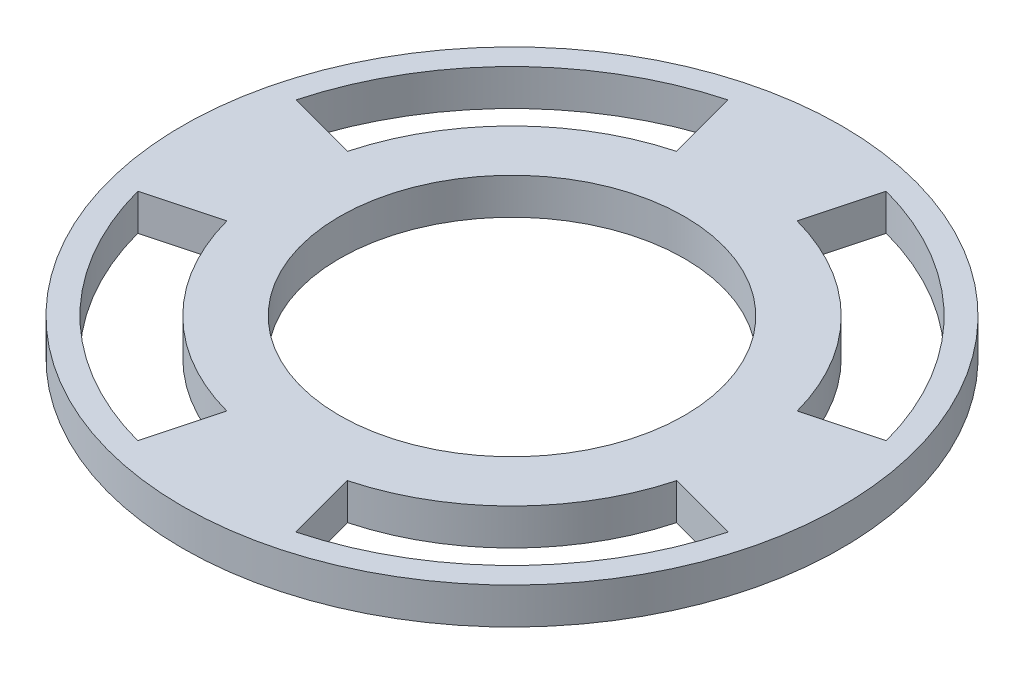
SolidWorks part; units mm, degrees
ref_plane "Front Plane" through (0, 0, 0) normal (0, 0, 1) x (1, 0, 0)
ref_plane "Top Plane" through (0, 0, 0) normal (0, 1, 0) x (1, 0, 0)
ref_plane "Right Plane" through (0, 0, 0) normal (1, 0, 0) x (0, 0, -1)
sketch "Sketch1" plane through (0, 0, 0) normal (0, 1, 0) x (1, 0, 0)
  line L0 (0, 0) -> (0, 22.65) construction
  line L1 (0, 0) -> (-5.8623, 21.8782)
  line L2 (0, 0) -> (5.8623, 21.8782)
  line L3 (0, 0) -> (21.8782, -5.8623)
  line L4 (0, 0) -> (21.8782, 5.8623)
  line L5 (0, 0) -> (-5.8623, -21.8782)
  line L6 (0, 0) -> (5.8623, -21.8782)
  line L7 (0, 0) -> (-21.8782, 5.8623)
  line L8 (0, 0) -> (-21.8782, -5.8623)
  circle A1 centre (0, 0) radius 11.85
  circle A2 centre (0, 0) radius 22.65
  circle A3 centre (0, 0) radius 21
  circle A4 centre (0, 0) radius 16
  point P17 (0, 0)
  dimension "D1" = 23.7
  dimension "D2" = 45.3
  dimension "D6" = 42
  dimension "D7" = 32
  dimension "D3" = 15
  dimension "D4" = 15
  dimension "D5" = 4
extrude "Boss-Extrude2" add sketch "Sketch1" along normal blind 2.5 contours A3 L1 A2 L7 | A3 L7 A2 L8 | A3 L8 A2 L5 | A3 L5 A2 L6 | A3 L6 A2 L3 | A3 L3 A2 L4 | A3 L4 A2 L2 | L0 A3 L2 A2 | A3 L0 A2 L1 | L1 A4 L7 A1 | L7 A4 L8 A1 | L5 A4 L6 A1 | L6 A4 L3 A1 | A4 L3 A3 L4 | L3 A4 L4 A1 | L0 A4 L2 A3 | A1 L0 A4 L1 | L0 A1 L2 A4 | L8 A4 L5 A1 | A4 L5 A3 L6 | A4 L0 A3 L1 | L4 A4 L2 A1 | A4 L7 A3 L8
